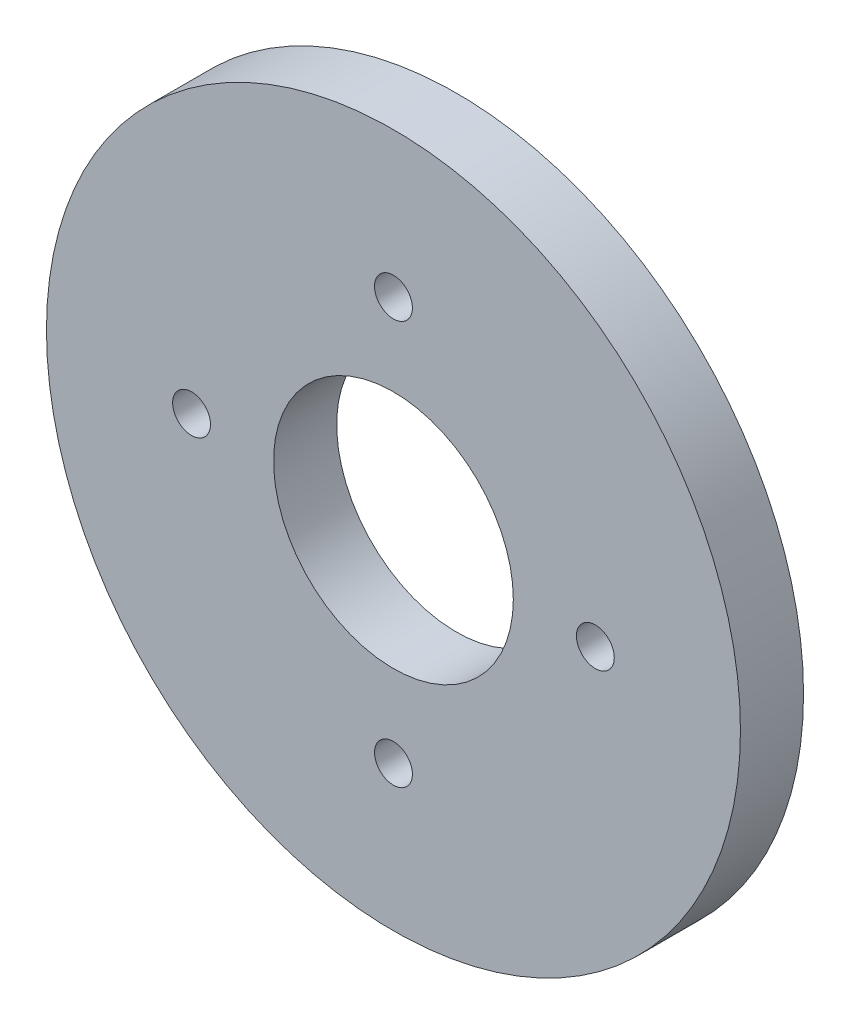
SolidWorks part; units mm, degrees
ref_plane "Plan de face" through (0, 0, 0) normal (0, 0, 1) x (1, 0, 0)
ref_plane "Plan de dessus" through (0, 0, 0) normal (0, 1, 0) x (1, 0, 0)
ref_plane "Plan de droite" through (0, 0, 0) normal (1, 0, 0) x (0, 0, -1)
sketch "Esquisse1" plane through (0, 0, 0) normal (0, 0, 1) x (1, 0, 0)
  circle A0 centre (0, 0) radius 27.5
  circle A1 centre (0, 0) radius 9.5
  dimension "D1" = 19
  dimension "D2" = 55
extrude "Boss.-Extru.1" add sketch "Esquisse1" along normal blind 5
sketch "Esquisse2" plane through (0, 0, 5) normal (0, 0, 1) x (1, 0, 0)
  circle A0 centre (16, 0) radius 1.5
  circle A1 centre (0, 16) radius 1.5
  circle A2 centre (0, -16) radius 1.5
  circle A3 centre (-16, 0) radius 1.5
  point P15 (0, 0)
  dimension "D1" = 3
  dimension "D3" = 16
  dimension "D2" = 4
extrude "Enlèv. mat.-Extru.2" cut sketch "Esquisse2" against normal blind 5
